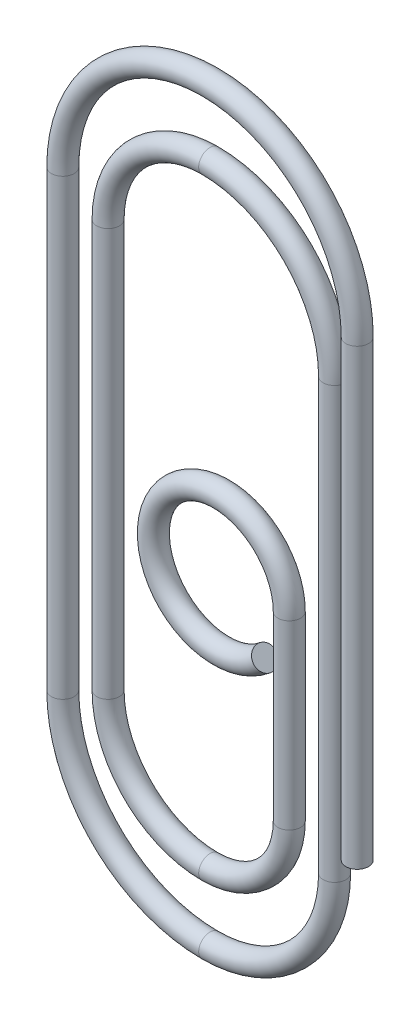
SolidWorks part; units mm, degrees
ref_plane "Спереди" through (0, 0, 0) normal (0, 0, 1) x (1, 0, 0)
ref_plane "Сверху" through (0, 0, 0) normal (0, 1, 0) x (1, 0, 0)
ref_plane "Справа" through (0, 0, 0) normal (1, 0, 0) x (0, 0, -1)
sketch "Эскиз1" plane through (0, 0, 0) normal (0, 0, 1) x (1, 0, 0)
  line L0 (-2.5, 40) -> (-2.5, -40) construction
  line L1 (15, 40) -> (15, -40) construction
  line L2 (-20, 40) -> (-20, -40) construction
  line L3 (-2.5, 55) -> (-2.5, -35) construction
  line L4 (20, 55) -> (20, -35) construction
  line L5 (-25, 55) -> (-25, -35) construction
  line L6 (-2.5, -45) -> (-2.5, 50) construction
  line L7 (-30, -45) -> (-30, 50) construction
  line L8 (25, -45) -> (25, 50) construction
  line L9 (-2.5, 60) -> (-2.5, -40) construction
  line L10 (30, 60) -> (30, -40) construction
  line L11 (-35, 60) -> (-35, -40) construction
  circle A0 centre (0, 0) radius 15 construction
  arc A1 (15, 40) -> (-20, 40) centre (-2.5, 40) ccw construction
  arc A2 (-20, -40) -> (15, -40) centre (-2.5, -40) ccw construction
  arc A3 (20, 55) -> (-25, 55) centre (-2.5, 55) ccw construction
  arc A4 (-25, -35) -> (20, -35) centre (-2.5, -35) ccw construction
  arc A5 (-30, -45) -> (25, -45) centre (-2.5, -45) ccw construction
  arc A6 (25, 50) -> (-30, 50) centre (-2.5, 50) ccw construction
  arc A7 (30, 60) -> (-35, 60) centre (-2.5, 60) ccw construction
  arc A8 (-35, -40) -> (30, -40) centre (-2.5, -40) ccw construction
  point P4 (-2.5, 0)
  point P11 (-2.5, 10)
  point P17 (-2.5, -57.5)
  point P20 (-2.5, 2.5)
  point P25 (-2.5, 77.5)
  point P28 (-2.5, 10)
  point P33 (-2.5, -72.5)
  dimension "D1" = 30
  dimension "D3" = 80
  dimension "D2" = 35
  dimension "D4" = 45
  dimension "D5" = 90
  dimension "D6" = 55
  dimension "D7" = 95
  dimension "D8" = 65
  dimension "D9" = 100
sketch "Эскиз2" plane through (0, 0, 0) normal (0, 0, 1) x (1, 0, 0)
  line L0 (15, 40) -> (15, -40) construction
  line L1 (15, 0) -> (15, -40)
  line L2 (-25, -35) -> (-25, 55)
  line L3 (25, 50) -> (25, -45)
  line L4 (-35, -40) -> (-35, 60)
  line L5 (30, 60) -> (30, -40)
  line L6 (0, 0) -> (9.6418, -11.4907) construction
  line L7 (0, 0) -> (0, -8.4286) construction
  arc A0 (9.6418, -11.4907) -> (15, 0) centre (0, 0) cw
  circle A1 centre (0, 0) radius 15 construction
  arc A2 (15, -40) -> (-2.5, -57.5) centre (-2.5, -40) cw
  arc A3 (-2.5, -57.5) -> (-25, -35) centre (-2.5, -35) cw
  arc A4 (-25, -35) -> (20, -35) centre (-2.5, -35) ccw construction
  arc A5 (-25, 55) -> (-2.5, 77.5) centre (-2.5, 55) cw
  arc A6 (-2.5, 77.5) -> (25, 50) centre (-2.5, 50) cw
  arc A7 (25, -45) -> (-2.5, -72.5) centre (-2.5, -45) cw
  arc A8 (-2.5, -72.5) -> (-35, -40) centre (-2.5, -40) cw
  arc A9 (-35, 60) -> (30, 60) centre (-2.5, 60) cw
  dimension "D1" = 40
ref_plane "Плоскость1" through (9.6418, -11.4907, 0) normal (0.766, 0.6428, 0) x (0, 0, -1)
sketch "Эскиз3" plane through (9.6418, -11.4907, 0) normal (0.766, 0.6428, 0) x (0, 0, -1)
  circle A0 centre (0, 0) radius 2.5
  dimension "D1" = 5
sweep "По траектории1" add profiles "Эскиз3" path "Эскиз2"
